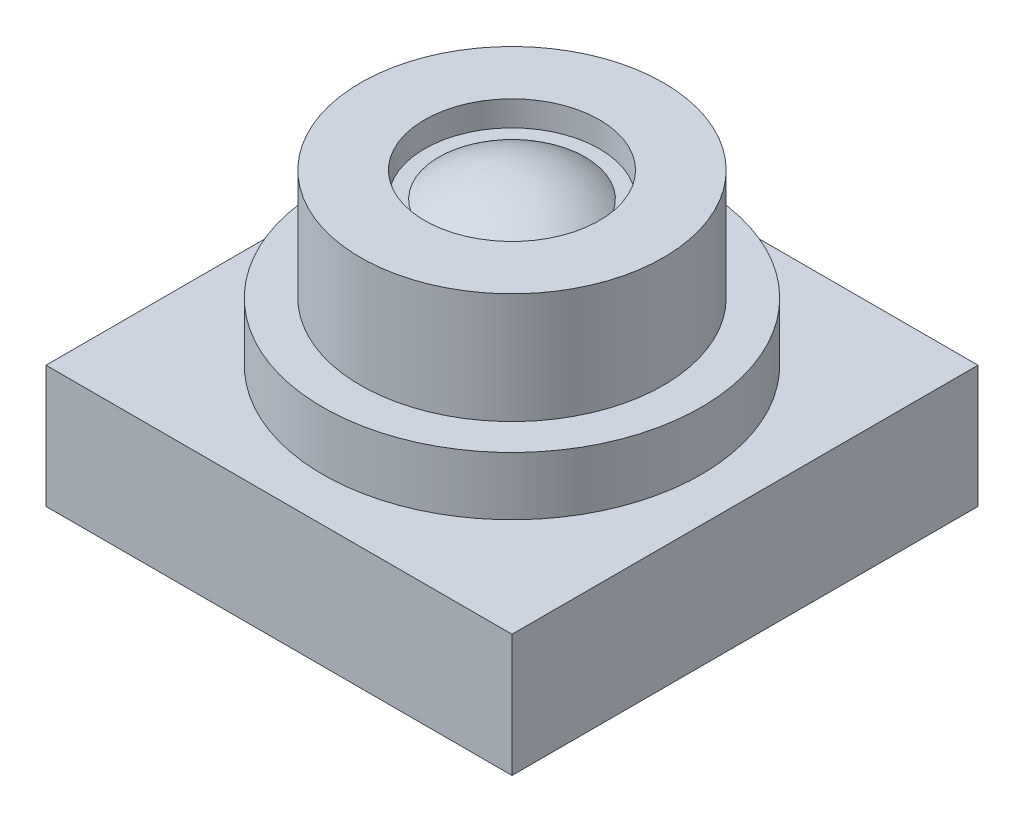
SolidWorks part; units mm, degrees
ref_plane "Front Plane" through (0, 0, 0) normal (0, 0, 1) x (1, 0, 0)
ref_plane "Top Plane" through (0, 0, 0) normal (0, 1, 0) x (1, 0, 0)
ref_plane "Right Plane" through (0, 0, 0) normal (1, 0, 0) x (0, 0, -1)
sketch "Sketch1" plane through (0, 0, 0) normal (0, 1, 0) x (1, 0, 0)
  line L0 (0, 6.0821) -> (0, -5.5245) construction
  line L1 (-4, -4) -> (4, -4)
  line L2 (-4, -4) -> (-4, 4)
  line L3 (-4, 4) -> (4, 4)
  line L4 (4, -4) -> (4, 4)
  line L5 (-5.8503, 0) -> (5.911, 0) construction
  dimension "D1" = 8
  dimension "D2" = 8
extrude "Boss-Extrude1" add sketch "Sketch1" along normal blind 2.1
sketch "Sketch2" plane through (0, 0, 0) normal (1, 0, 0) x (0, 0, -1)
  line L0 (-3.25, 2.1) -> (-3.25, 3.1)
  line L1 (-4, 2.1) -> (4, 2.1) construction
  line L2 (-3.25, 3.1) -> (-2.6, 3.1)
  line L3 (-2.6, 3.1) -> (-2.6, 5)
  line L4 (-2.6, 5) -> (-1.5, 5)
  line L8 (0, 0) -> (0, 8.4536) construction
  line L9 (-4, 0) -> (4, 0) construction
  line L10 (0, 5) -> (0, 2.1)
  line L11 (0, 2.1) -> (-3.25, 2.1)
  line L12 (-0.7439, 0.3) -> (-8.1353, 0.3) construction
  line L13 (-1.5, 5) -> (-1.5, 4.5681)
  line L14 (-1.5, 4.5681) -> (-1.2554, 4.5681)
  arc A0 (0, 5) -> (-1.2554, 4.5681) centre (0, 2.9597) ccw
  dimension "D1" = 6.5
  dimension "D2" = 5.2
  dimension "D3" = 3.1
  dimension "D4" = 2.8
  dimension "D5" = 5
  dimension "D6" = 3
revolve "Revolve1" add sketch "Sketch2" angle 360 about L8
